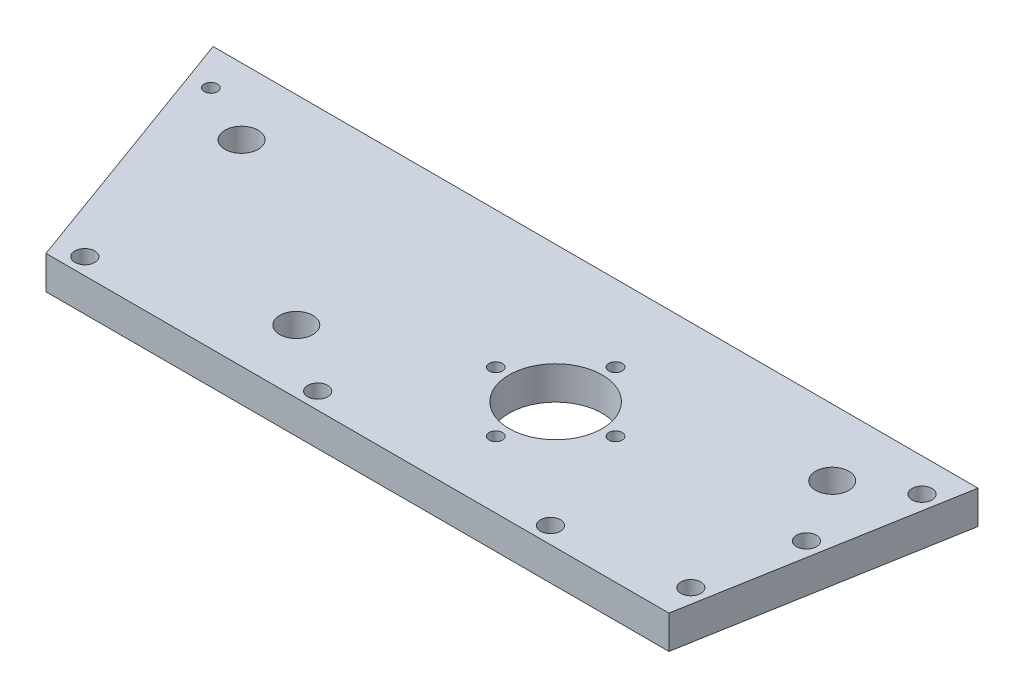
SolidWorks part; units mm, degrees
material "6061-T6 (SS)"
ref_plane "Front Plane" through (0, 0, 0) normal (1, 0, 0) x (0, 1, 0)
ref_plane "Top Plane" through (0, 0, 0) normal (0, 0, 1) x (0, 1, 0)
ref_plane "Right Plane" through (0, 0, 0) normal (0, 1, 0) x (-1, 0, 0)
sketch "Sketch1" plane through (0, 0, 0) normal (0, 1, 0) x (-1, 0, 0)
  line L0 (-72.4911, -52.5) -> (42.5089, -52.5)
  line L1 (42.5089, -52.5) -> (28.1321, -13)
  line L4 (28.1321, -13) -> (-65.5261, -13)
  line L5 (-65.5261, -13) -> (-72.4911, -52.5)
  arc A1 (-18.3644, -13) -> (18.3644, -13) centre (0, 0) ccw construction
  point P25 (-19.0329, 12)
  point P28 (19.0329, 12)
  point P31 (-18.3644, -13)
  dimension "D2" = 45
  dimension "D3" = 13
  dimension "D4" = 28.1321
  dimension "D5" = 39.5
  dimension "D6" = 115
  dimension "D8" = 13
  dimension "D9" = 80
  dimension "D10" = 70
extrude "Boss-Extrude2" add sketch "Sketch1" along normal blind 5
sketch "Sketch2" plane through (0, 5, 0) normal (0, 1, 0) x (-1, 0, 0)
  line L0 (42.5089, -52.5) -> (28.1321, -13) construction
  line L1 (-72.4911, -52.5) -> (42.5089, -52.5) construction
  line L5 (-72.4911, -52.5) -> (42.5089, -52.5) construction
  line L6 (-65.5261, -13) -> (-72.4911, -52.5) construction
  circle A0 centre (28.2275, -42.5) radius 10 construction
  circle A1 centre (28.2275, -42.5) radius 2.5
  circle A2 centre (0, -22.5) radius 2.5
  circle A3 centre (-60.5735, -42.5) radius 10 construction
  circle A4 centre (-60.5735, -42.5) radius 2.5
  circle A5 centre (0, 0) radius 22.5 construction
  dimension "D1" = 20
  dimension "D2" = 5
  dimension "D4" = 5
  dimension "D5" = 20
  dimension "D6" = 5
extrude "Cut-Extrude1" cut sketch "Sketch2" against normal blind 5 contours A4 | A2 | A1
sketch "Sketch3" plane through (0, 5, 0) normal (0, 1, 0) x (1, 0, 0)
  line L2 (68.8764, 32) -> (-35.0476, 32) construction
  line L3 (65.5261, 13) -> (72.4911, 52.5) construction
  line L4 (-42.5089, 52.5) -> (-28.1321, 13) construction
  line L5 (72.4911, 52.5) -> (-42.5089, 52.5) construction
  circle A9 centre (29.4911, 32) radius 7
  circle A15 centre (0, 22.5) radius 15 construction
  circle A18 centre (-28.2275, 42.5) radius 15 construction
  circle A19 centre (60.5735, 42.5) radius 15 construction
  circle A20 centre (29.4911, 32) radius 22.5 construction
  circle A21 centre (29.4911, 32) radius 9 construction
  circle A22 centre (20.4911, 32) radius 1
  circle A23 centre (29.4911, 41) radius 1
  circle A24 centre (38.4911, 32) radius 1
  circle A25 centre (29.4911, 23) radius 1
  dimension "D1" = 14
  dimension "D2" = 30
  dimension "D4" = 30
  dimension "D6" = 45
  dimension "D9" = 4
  dimension "D8" = 2
  dimension "D3" = 30
  dimension "D7" = 18
  dimension "D5" = 20.5
  dimension "D10" = 43
extrude "Cut-Extrude2" cut sketch "Sketch3" against normal through all
sketch "Sketch4" plane through (0, 0, 0) normal (0, -1, 0) x (1, 0, 0)
  line L0 (65.5261, -13) -> (72.4911, -52.5) construction
  line L1 (72.4911, -52.5) -> (-42.5089, -52.5) construction
  line L2 (-28.1321, -13) -> (65.5261, -13) construction
  line L3 (-42.5089, -52.5) -> (-28.1321, -13) construction
  circle A0 centre (69.0709, -47.5) radius 1.5
  circle A6 centre (66.4661, -32.7279) radius 1.5
  circle A7 centre (63.8614, -17.9558) radius 1.5
  circle A8 centre (-24.7853, -15.5) radius 1.5
  circle A9 centre (10.2147, -15.5) radius 1.5
  circle A10 centre (45.2147, -15.5) radius 1.5
  dimension "D1" = 3
  dimension "D4" = 3
  dimension "D2" = 2.5
  dimension "D3" = 5
  dimension "D5" = 2.5
  dimension "D6" = 4
extrude "Cut-Extrude3" cut sketch "Sketch4" against normal through all contours A8 | A9 | A10 | A7 | A6 | A0
sketch "Sketch5" plane through (0, 5, 0) normal (0, 1, 0) x (-1, 0, 0)
  circle A0 centre (37.2957, -46.9482) radius 1
  point P2 (0, 0)
  point P3 (37.2957, -46.9482)
  point P6 (34.2848, -46.95)
  dimension "D1" = 2
extrude "Cut-Extrude4" cut sketch "Sketch5" against normal through all contours A0
